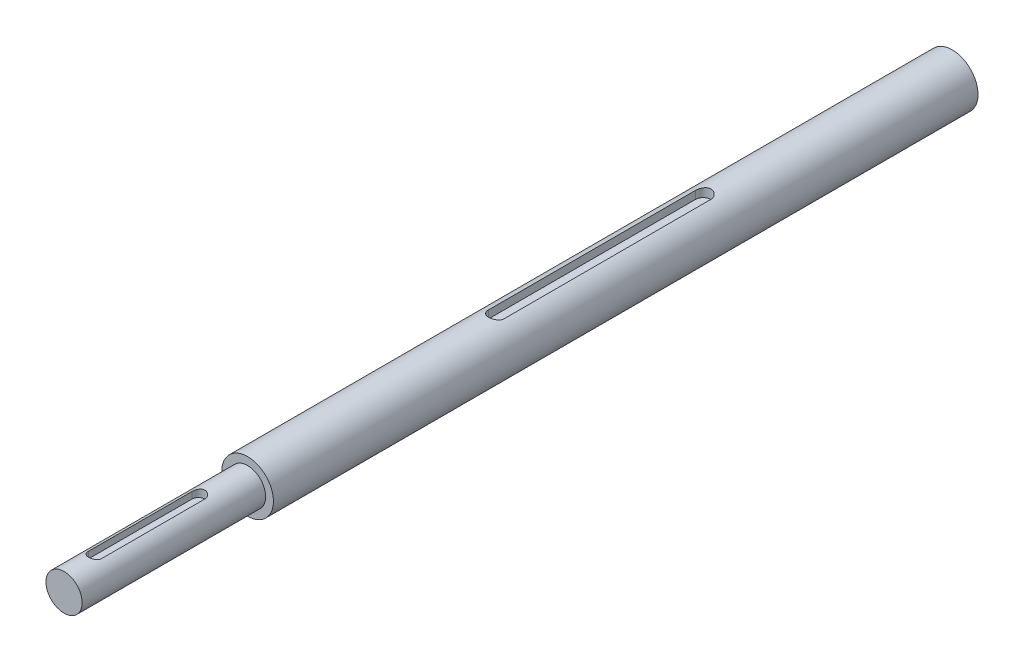
SolidWorks part; units mm, degrees
ref_plane "Ön Düzlem" through (0, 0, 0) normal (0, 0, 1) x (1, 0, 0)
ref_plane "Üst Düzlem" through (0, 0, 0) normal (0, 1, 0) x (1, 0, 0)
ref_plane "Sağ Düzlem" through (0, 0, 0) normal (1, 0, 0) x (0, 0, -1)
sketch "Çizim1" plane through (0, 0, 0) normal (0, 0, 1) x (1, 0, 0)
  circle A0 centre (0, 0) radius 10
  dimension "D1" = 20
extrude "Yükseklik-Ekstrüzyon1" add sketch "Çizim1" along normal mid plane 272.6
sketch "Çizim2" plane through (0, 0, 136.3) normal (0, 0, 1) x (1, 0, 0)
  circle A0 centre (0, 0) radius 7
  dimension "D1" = 14
extrude "Yükseklik-Ekstrüzyon2" add sketch "Çizim2" along normal blind 71
ref_plane "Düzlem1" through (0, 7, 0) normal (0, 1, 0) x (1, 0, 0)
sketch "Çizim3" plane through (0, 7, 0) normal (0, 1, 0) x (1, 0, 0)
  line L0 (0, -155.3) -> (0, -195.3) construction
  line L1 (2.5, -155.3) -> (2.5, -195.3)
  line L2 (-2.5, -155.3) -> (-2.5, -195.3)
  line L3 (-7, -207.3) -> (7, -207.3) construction
  arc A0 (2.5, -155.3) -> (-2.5, -155.3) centre (0, -155.3) ccw
  arc A1 (-2.5, -195.3) -> (2.5, -195.3) centre (0, -195.3) ccw
  point P3 (0, -175.3)
  dimension "D1" = 40
  dimension "D2" = 5
  dimension "D3" = 12
extrude "Kes-Ekstrüzyon1" cut sketch "Çizim3" against normal blind 3
ref_plane "Düzlem2" through (0, 10, 0) normal (0, 1, 0) x (1, 0, 0)
sketch "Çizim4" plane through (0, 10, 0) normal (0, 1, 0) x (1, 0, 0)
  line L0 (0, -40) -> (0, 40) construction
  line L1 (-3, -40) -> (-3, 40)
  line L2 (3, -40) -> (3, 40)
  arc A0 (-3, -40) -> (3, -40) centre (0, -40) ccw
  arc A1 (3, 40) -> (-3, 40) centre (0, 40) ccw
  point P2 (0, 0)
  dimension "D1" = 80
  dimension "D2" = 6
extrude "Kes-Ekstrüzyon2" cut sketch "Çizim4" against normal blind 3.5
